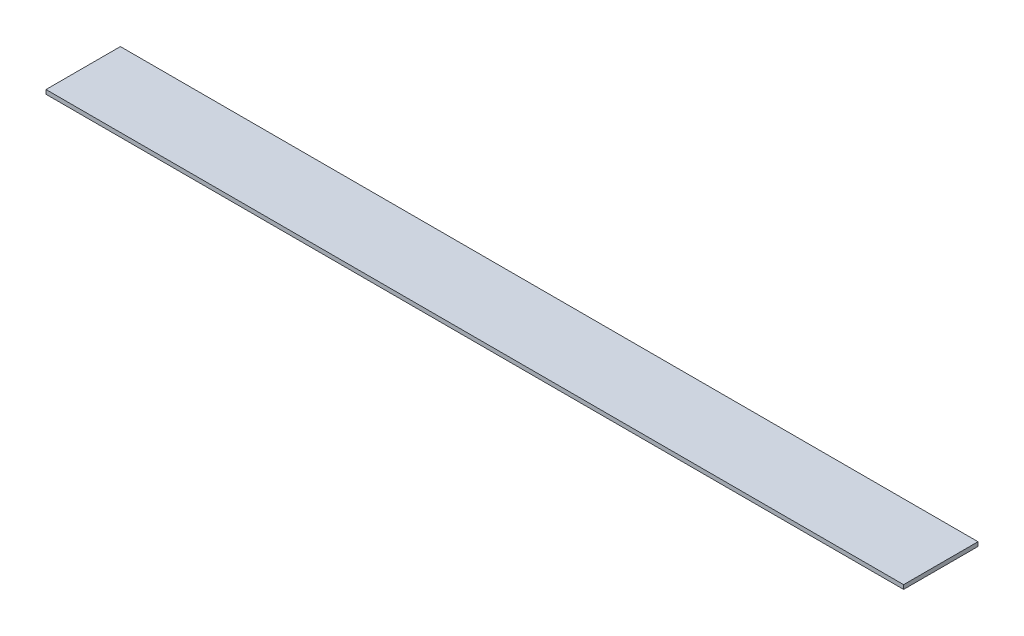
SolidWorks part; units mm, degrees
ref_plane "Front Plane" through (0, 0, 0) normal (0, 0, 1) x (1, 0, 0)
ref_plane "Top Plane" through (0, 0, 0) normal (0, 1, 0) x (1, 0, 0)
ref_plane "Right Plane" through (0, 0, 0) normal (1, 0, 0) x (0, 0, -1)
sketch "Sketch1" plane through (0, 0, 0) normal (0, 1, 0) x (1, 0, 0)
  line L1 (0, 0) -> (392, 0)
  line L2 (0, 0) -> (0, 34)
  line L3 (0, 34) -> (392, 34)
  line L4 (392, 0) -> (392, 34)
  dimension "D1" = 34
  dimension "D2" = 392
extrude "Boss-Extrude1" add sketch "Sketch1" along normal blind 1.9
